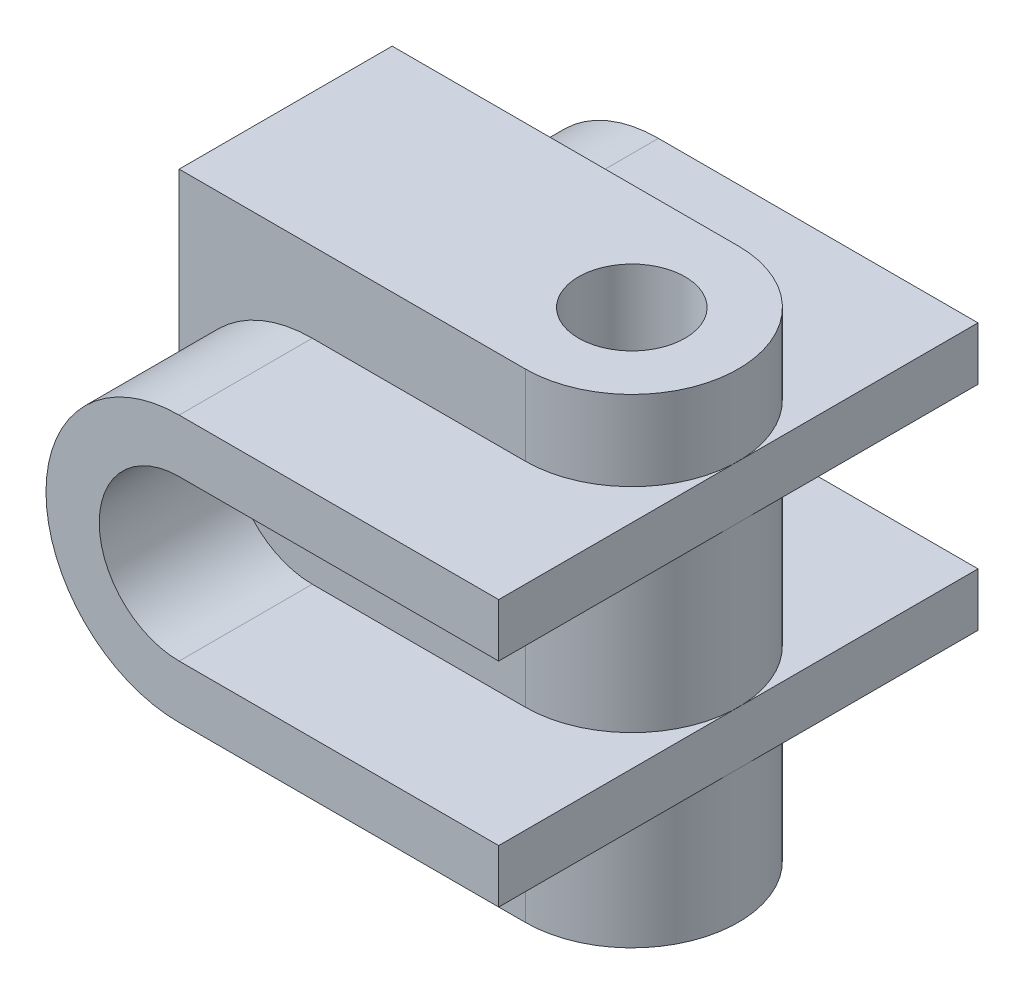
SolidWorks part; units mm, degrees
ref_plane "Front" through (0, 0, 0) normal (0, 0, 1) x (1, 0, 0)
ref_plane "Top" through (0, 0, 0) normal (0, 1, 0) x (1, 0, 0)
ref_plane "Right" through (0, 0, 0) normal (1, 0, 0) x (0, 0, -1)
other "Configuration Table"
sketch "Sketch1" plane through (0, 0, 0) normal (0, 0, 1) x (1, 0, 0)
  line L0 (0, -15) -> (-60, -15)
  line L1 (-60, -65) -> (0, -65)
  arc A0 (-60, -15) -> (-60, -65) centre (-60, -40) ccw
  dimension "D3" = 25
  dimension "D1" = 15
  dimension "D2" = 60
extrude "Extrude-Thin1" add sketch "Sketch1" along normal blind 90 thin thin type one direction reverse wall 10
sketch "Sketch2" plane through (0, 0, 0) normal (0, 1, 0) x (1, 0, 0)
  line L0 (-85, -25) -> (-85, -65)
  line L1 (-85, 0) -> (-85, -90) construction
  line L2 (-85, -65) -> (-20, -65)
  line L3 (-20, -25) -> (-85, -25)
  line L4 (0, -90) -> (0, 0) construction
  arc A0 (-20, -65) -> (-20, -25) centre (-20, -45) ccw
  circle A1 centre (-20, -45) radius 10
  dimension "D2" = 25
  dimension "D3" = 20
  dimension "D1" = 40
extrude "Boss-Extrude1" add sketch "Sketch2" against normal blind 90 separate body
split "official_split_multi_inter" trim tools "Top" bodies to split 102 101 resulting bodies 103 104
